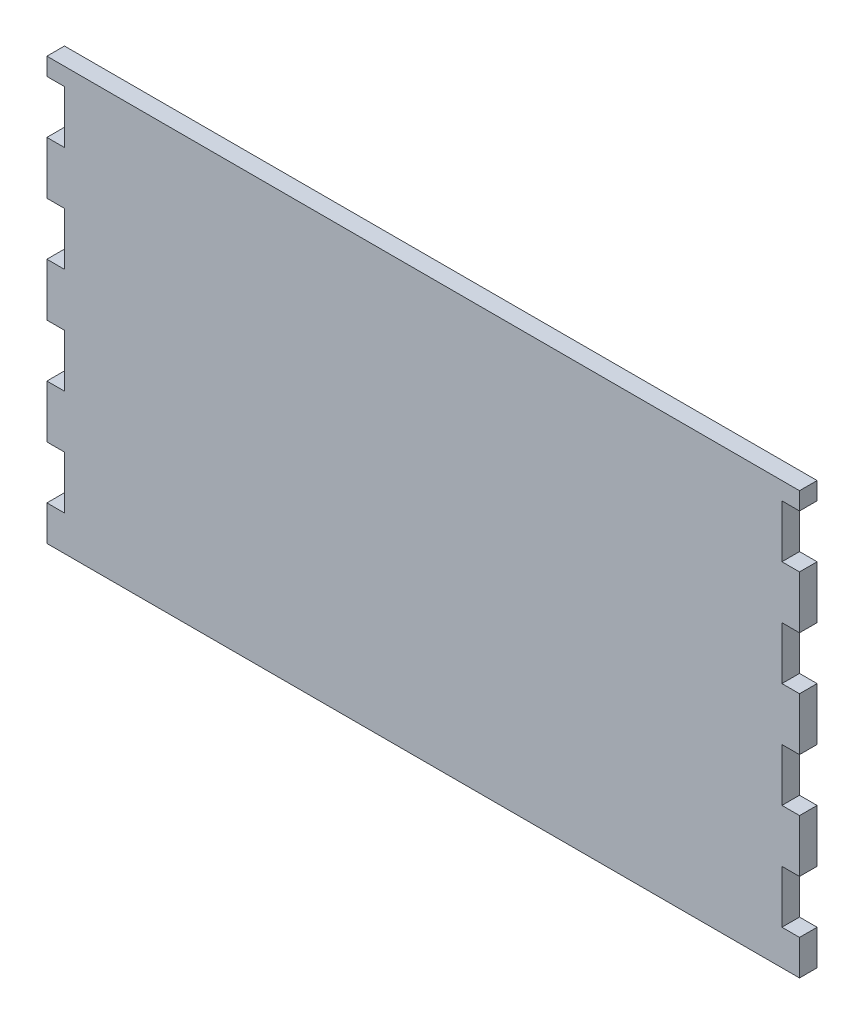
SolidWorks part; units mm, degrees
ref_plane "Front Plane" through (0, 0, 0) normal (0, 0, 1) x (1, 0, 0)
ref_plane "Top Plane" through (0, 0, 0) normal (0, 1, 0) x (1, 0, 0)
ref_plane "Right Plane" through (0, 0, 0) normal (1, 0, 0) x (0, 0, -1)
sketch "Sketch1" plane through (0, 0, 0) normal (0, 0, 1) x (1, 0, 0)
  line L1 (135.89, -76.2) -> (-135.89, -76.2)
  line L2 (135.89, -76.2) -> (135.89, 76.2)
  line L3 (135.89, 76.2) -> (-135.89, 76.2)
  line L4 (-135.89, -76.2) -> (-135.89, 76.2)
  line L5 (135.89, -76.2) -> (-135.89, 76.2) construction
  line L6 (135.89, 76.2) -> (-135.89, -76.2) construction
  point P0 (0, 0)
  dimension "D1" = 271.78
  dimension "D2" = 152.4
extrude "Boss-Extrude1" add sketch "Sketch1" along normal blind 6.35
sketch "Sketch2" plane through (0, 0, 6.35) normal (0, 0, 1) x (1, 0, 0)
  line L0 (-135.89, 76.2) -> (-135.89, -76.2) construction
  line L1 (-135.89, 69.85) -> (-129.54, 69.85)
  line L2 (-135.89, 69.85) -> (-135.89, 50.8)
  line L3 (-135.89, 50.8) -> (-129.54, 50.8)
  line L4 (-129.54, 69.85) -> (-129.54, 50.8)
  line L5 (135.89, 76.2) -> (-135.89, 76.2) construction
  point P6 (0, 0)
  dimension "D1" = 6.35
  dimension "D2" = 19.05
  dimension "D3" = 6.35
extrude "Cut-Extrude1" cut sketch "Sketch2" against normal through all
pattern_linear "LPattern1" count 4 spacing 38.1 along (0, -1, 0) of "Cut-Extrude1"
mirror "Mirror1" about plane through (0, 0, 0) normal (1, 0, 0) of "LPattern1", "Cut-Extrude1"
